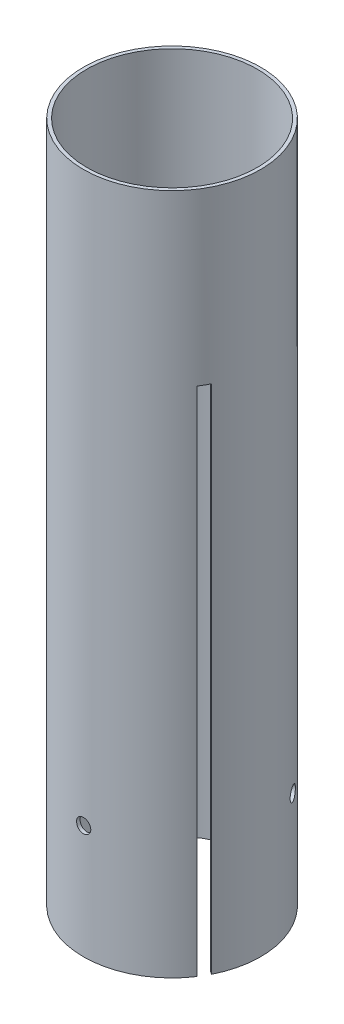
SolidWorks part; units mm, degrees
material "S-Glass Fiber"
ref_plane "Front Plane" through (0, 0, 0) normal (0, 0, 1) x (1, 0, 0)
ref_plane "Top Plane" through (0, 0, 0) normal (0, 1, 0) x (1, 0, 0)
ref_plane "Right Plane" through (0, 0, 0) normal (1, 0, 0) x (0, 0, -1)
sketch "Sketch2" plane through (0, 0, 0) normal (0, 1, 0) x (1, 0, 0)
  circle A0 centre (0, 0) radius 39.624
  circle A1 centre (0, 0) radius 38.1
  dimension "D1" = 79.248
  dimension "D2" = 76.2
extrude "Boss-Extrude1" add sketch "Sketch2" along normal blind 304.8 contours A1 | A0
sketch "Sketch3" plane through (0, 0, 0) normal (0, 0, 1) x (1, 0, 0)
  line L0 (-2.3812, 0) -> (2.3812, 0)
  line L1 (-39.624, 0) -> (39.624, 0) construction
  line L2 (2.3812, 0) -> (2.3812, 228.6)
  line L3 (2.3812, 228.6) -> (-2.3813, 228.6)
  line L4 (-2.3813, 228.6) -> (-2.3812, 0)
  point P6 (0, 0)
  dimension "D1" = 4.7625
  dimension "D2" = 228.6
extrude "Cut-Extrude1" cut sketch "Sketch3" against normal through all
pattern_circular "CirPattern1" count 3 over 360 about axis through (0, 0, 0) along (0, 1, 0) of "Cut-Extrude1"
sketch "Sketch4" plane through (0, 0, 0) normal (0, 0, 1) x (1, 0, 0)
  line L0 (-33.0627, 0) -> (33.0627, 0) construction
  circle A0 centre (0, 50.8) radius 3.175
  dimension "D1" = 6.35
  dimension "D2" = 50.8
extrude "Cut-Extrude3" cut sketch "Sketch4" along normal through all
pattern_circular "CirPattern2" count 3 over 360 about axis through (0, 304.8, 0) along (0, -1, 0) of "Cut-Extrude3"
